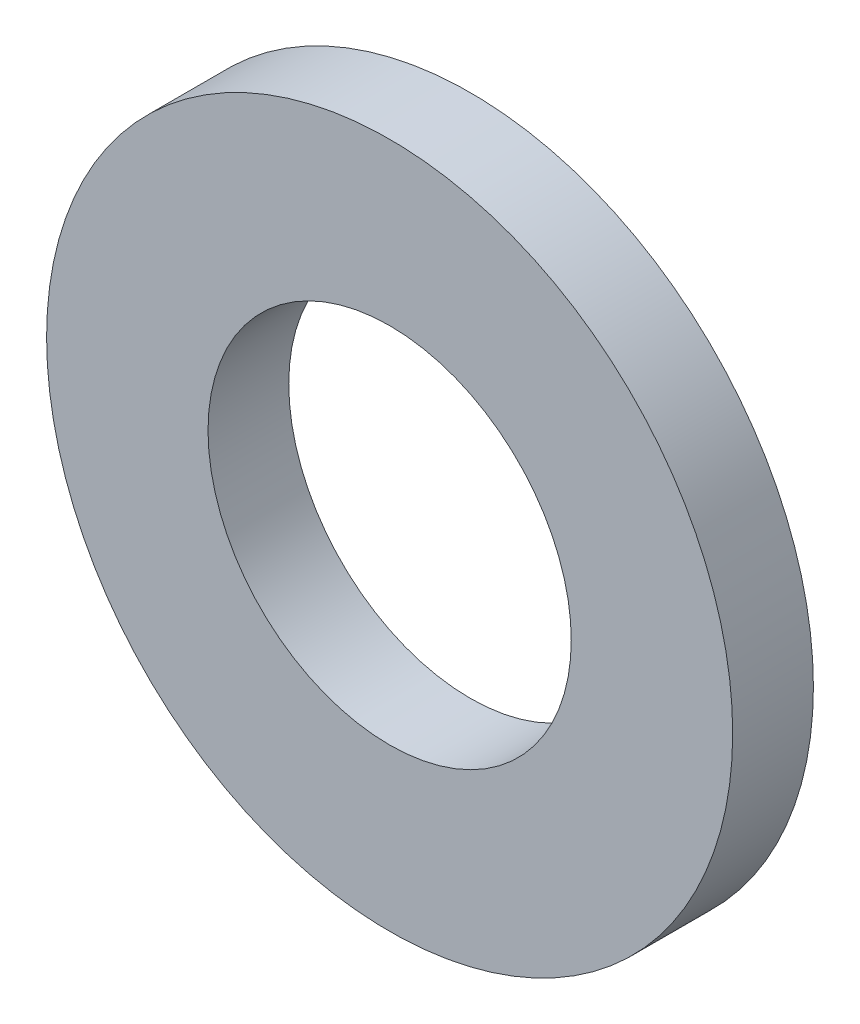
SolidWorks part; units mm, degrees
ref_plane "Front Plane" through (0, 0, 0) normal (0, 0, 1) x (1, 0, 0)
ref_plane "Top Plane" through (0, 0, 0) normal (0, 1, 0) x (1, 0, 0)
ref_plane "Right Plane" through (0, 0, 0) normal (1, 0, 0) x (0, 0, -1)
sketch "Sketch1" plane through (0, 0, 0) normal (0, 0, 1) x (1, 0, 0)
  circle A0 centre (0, 0) radius 2.25
  circle A1 centre (0, 0) radius 4.25
  dimension "D1" = 4.5
  dimension "D2" = 8.5
extrude "Boss-Extrude1" add sketch "Sketch1" along normal blind 1
